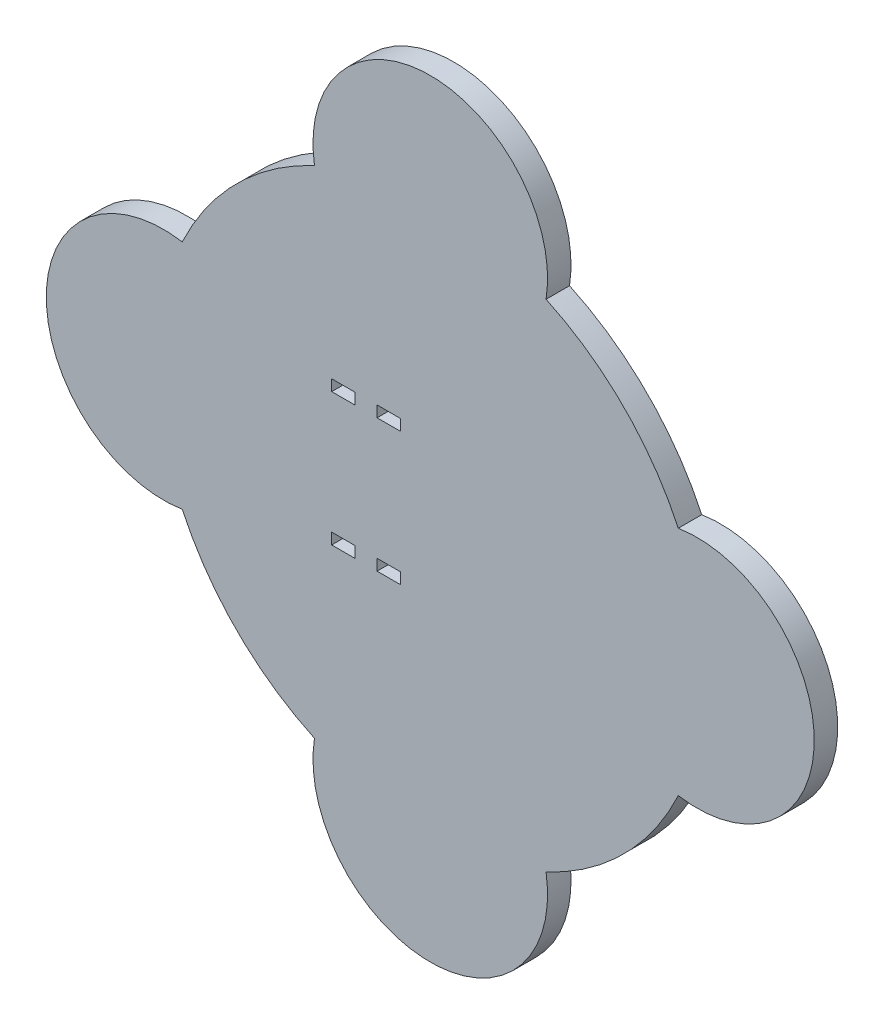
SolidWorks part; units mm, degrees
ref_plane "Alzado" through (0, 0, 0) normal (0, 0, 1) x (1, 0, 0)
ref_plane "Planta" through (0, 0, 0) normal (0, 1, 0) x (1, 0, 0)
ref_plane "Vista lateral" through (0, 0, 0) normal (1, 0, 0) x (0, 0, -1)
sketch "Croquis1" plane through (0, 0, 0) normal (0, 0, 1) x (1, 0, 0)
  line L0 (0, 0) -> (0, 49.1038) construction
  arc A0 (-31.713, -14.8083) -> (-14.8083, -31.713) centre (0, 0) ccw
  arc A1 (-14.8083, 31.713) -> (14.8083, 31.713) centre (0, 34.1038) cw
  arc A2 (31.713, 14.8083) -> (31.713, -14.8083) centre (34.1038, 0) cw
  arc A3 (14.8083, -31.713) -> (-14.8083, -31.713) centre (0, -34.1038) cw
  arc A4 (-31.713, -14.8083) -> (-31.713, 14.8083) centre (-34.1038, 0) cw
  arc A5 (14.8083, -31.713) -> (31.713, -14.8083) centre (0, 0) ccw
  arc A6 (31.713, 14.8083) -> (14.8083, 31.713) centre (0, 0) ccw
  arc A7 (-14.8083, 31.713) -> (-31.713, 14.8083) centre (0, 0) ccw
  point P8 (0, 49.1038)
  point P20 (0, 0)
  dimension "D1" = 70
  dimension "D2" = 15
  dimension "D3" = 49.1038
  dimension "D4" = 4
extrude "Saliente-Extruir1" add sketch "Croquis1" along normal blind 3
sketch "Croquis2" plane through (0, 0, 3) normal (0, 0, 1) x (1, 0, 0)
  line L0 (-49.1038, 0) -> (49.1038, 0) construction
  line L1 (-8.2038, -34.025) -> (-8.2038, 34.025) construction
  line L2 (-12.6038, 9.9) -> (-9.6038, 9.9)
  line L3 (-9.6038, 9.9) -> (-9.6038, -9.9)
  line L4 (-9.6038, -9.9) -> (-12.6038, -9.9)
  line L5 (-3.8038, 9.9) -> (-6.8038, 9.9)
  line L6 (-3.8038, -9.9) -> (-3.8038, 9.9)
  line L7 (-6.8038, 9.9) -> (-6.8038, -9.9)
  line L8 (-12.6038, -9.9) -> (-12.6038, 9.9)
  line L9 (-6.8038, -9.9) -> (-3.8038, -9.9)
  arc A0 (-31.713, 14.8083) -> (-31.713, -14.8083) centre (-34.1038, 0) ccw construction
  arc A1 (31.713, -14.8083) -> (31.713, 14.8083) centre (34.1038, 0) ccw construction
  arc A2 (-31.713, -14.8083) -> (-14.8083, -31.713) centre (0, 0) ccw construction
  arc A3 (-14.8083, 31.713) -> (-31.713, 14.8083) centre (0, 0) ccw construction
  dimension "D1" = 19.8
  dimension "D2" = 3
  dimension "D3" = 36.5
  dimension "D4" = 1.4
sketch "Croquis4" plane through (0, 0, 3) normal (0, 0, 1) x (1, 0, 0)
  line L0 (-5.3038, -48.1348) -> (-5.3038, 48.1348) construction
  line L2 (-49.1038, 0) -> (49.1038, 0) construction
  line L3 (-6.8038, -9.202) -> (-3.8038, -9.202)
  line L4 (-6.8038, -9.202) -> (-6.8038, -7.7795)
  line L5 (-11.1038, -44.1887) -> (-11.1038, 44.1887) construction
  line L7 (-6.8038, -7.7795) -> (-3.8038, -7.7795)
  line L8 (-3.8038, -9.202) -> (-3.8038, -7.7795)
  line L9 (-6.8038, -9.202) -> (-3.8038, -7.7795) construction
  line L10 (-6.8038, -7.7795) -> (-3.8038, -9.202) construction
  line L11 (-3.8038, 9.202) -> (-3.8038, 7.7795)
  line L12 (-6.8038, 7.7795) -> (-3.8038, 7.7795)
  line L13 (-6.8038, 9.202) -> (-6.8038, 7.7795)
  line L14 (-6.8038, 9.202) -> (-3.8038, 9.202)
  line L15 (-8.2038, 46.6616) -> (-8.2038, -46.6616) construction
  line L16 (-9.6038, 9.202) -> (-9.6038, 7.7795)
  line L23 (-9.6038, 9.202) -> (-12.6038, 9.202)
  line L24 (-12.6038, 9.202) -> (-12.6038, 7.7795)
  line L25 (-9.6038, 7.7795) -> (-12.6038, 7.7795)
  line L30 (-9.6038, -9.202) -> (-9.6038, -7.7795)
  line L31 (-9.6038, -7.7795) -> (-12.6038, -7.7795)
  line L32 (-12.6038, -9.202) -> (-12.6038, -7.7795)
  line L33 (-9.6038, -9.202) -> (-12.6038, -9.202)
  arc A0 (-14.8083, -31.713) -> (14.8083, -31.713) centre (0, -34.1038) ccw construction
  arc A1 (14.8083, 31.713) -> (-14.8083, 31.713) centre (0, 34.1038) ccw construction
  arc A2 (-31.713, 14.8083) -> (-31.713, -14.8083) centre (-34.1038, 0) ccw construction
  arc A3 (31.713, -14.8083) -> (31.713, 14.8083) centre (34.1038, 0) ccw construction
  point P3 (-5.3038, -8.4907)
  point P36 (-5.3038, 0)
  dimension "D1" = 5.3038
  dimension "D2" = 11.1038
  dimension "D3" = 1.4225
  dimension "D4" = 3
  dimension "D5" = 9.202
  dimension "D6" = 2.9
extrude "Cortar-Extruir1" cut sketch "Croquis4" against normal up to next
